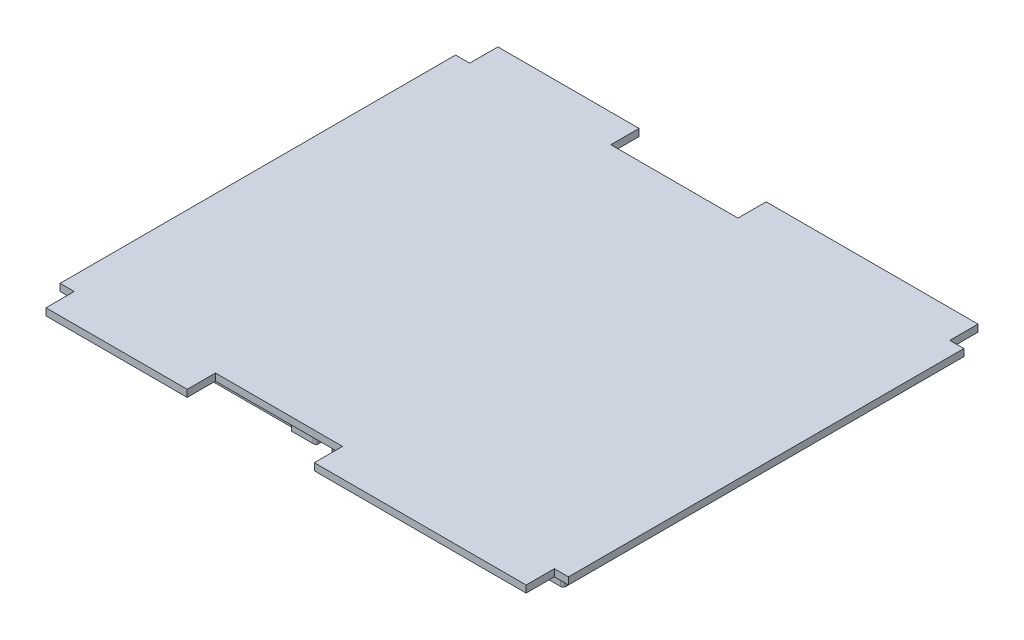
SolidWorks part; units mm, degrees
material "6061 Alloy"
ref_plane "Front Plane" through (0, 0, 0) normal (0, 0, 1) x (1, 0, 0)
ref_plane "Top Plane" through (0, 0, 0) normal (0, 1, 0) x (1, 0, 0)
ref_plane "Right Plane" through (0, 0, 0) normal (1, 0, 0) x (0, 0, -1)
sketch "Sketch1" plane through (0, 0, 0) normal (0, 1, 0) x (1, 0, 0)
  line L0 (410.2845, 0) -> (-410.2845, 0) construction
  line L1 (228.6, 177.8) -> (-228.6, 177.8) construction
  line L2 (228.6, 177.8) -> (228.6, -177.8) construction
  line L3 (228.6, -177.8) -> (-228.6, -177.8) construction
  line L4 (-228.6, 177.8) -> (-228.6, -177.8) construction
  line L5 (228.6, 177.8) -> (-228.6, -177.8) construction
  line L6 (228.6, -177.8) -> (-228.6, 177.8) construction
  line L7 (-215.9, -177.8) -> (-88.9, -177.8) construction
  line L8 (-215.9, -177.8) -> (-215.9, -203.2) construction
  line L9 (-88.9, -177.8) -> (-88.9, -203.2) construction
  line L10 (-215.9, -203.2) -> (-88.9, -203.2) construction
  line L11 (215.9, -177.8) -> (25.4, -177.8) construction
  line L12 (215.9, -177.8) -> (215.9, -203.2) construction
  line L13 (25.4, -177.8) -> (25.4, -203.2) construction
  line L14 (215.9, -203.2) -> (25.4, -203.2) construction
  line L15 (-228.6, 177.8) -> (-228.6, -177.8)
  line L16 (-228.6, -177.8) -> (-215.9, -177.8)
  line L17 (-215.9, -177.8) -> (-215.9, -203.2)
  line L18 (-215.9, -203.2) -> (-88.9, -203.2)
  line L19 (-88.9, -203.2) -> (-88.9, -177.8)
  line L20 (-88.9, -177.8) -> (25.4, -177.8)
  line L21 (25.4, -177.8) -> (25.4, -203.2)
  line L22 (25.4, -203.2) -> (215.9, -203.2)
  line L23 (215.9, -203.2) -> (215.9, -177.8)
  line L24 (215.9, -177.8) -> (228.6, -177.8)
  line L25 (228.6, -177.8) -> (228.6, 177.8)
  line L26 (215.9, 203.2) -> (25.4, 203.2) construction
  line L27 (25.4, 177.8) -> (25.4, 203.2) construction
  line L28 (215.9, 177.8) -> (215.9, 203.2) construction
  line L29 (215.9, 177.8) -> (25.4, 177.8) construction
  line L30 (-215.9, 203.2) -> (-88.9, 203.2) construction
  line L31 (-88.9, 177.8) -> (-88.9, 203.2) construction
  line L32 (-215.9, 177.8) -> (-215.9, 203.2) construction
  line L33 (-215.9, 177.8) -> (-88.9, 177.8) construction
  line L34 (228.6, 177.8) -> (-228.6, 177.8) construction
  line L35 (215.9, 177.8) -> (228.6, 177.8)
  line L36 (215.9, 203.2) -> (215.9, 177.8)
  line L37 (25.4, 203.2) -> (215.9, 203.2)
  line L38 (25.4, 177.8) -> (25.4, 203.2)
  line L39 (-88.9, 177.8) -> (25.4, 177.8)
  line L40 (-88.9, 203.2) -> (-88.9, 177.8)
  line L41 (-215.9, 203.2) -> (-88.9, 203.2)
  line L42 (-215.9, 177.8) -> (-215.9, 203.2)
  line L43 (-228.6, 177.8) -> (-215.9, 177.8)
  point P0 (0, 0)
  point P6 (-215.9, -177.8)
  point P7 (215.9, -177.8)
  point P8 (-215.9, -190.5)
  point P11 (0, 0)
  point P22 (-228.6, 0)
  point P30 (228.6, 0)
  dimension "D1" = 355.6
  dimension "D2" = 457.2
  dimension "D3" = 12.7
  dimension "D4" = 12.7
  dimension "D5" = 25.4
  dimension "D6" = 25.4
  dimension "D7" = 127
  dimension "D8" = 190.5
extrude "Boss-Extrude1" add sketch "Sketch1" along normal blind 6.35
sketch "Sketch2" plane through (0, 0, 0) normal (0, -1, 0) x (1, 0, 0)
  line L0 (0, 0) -> (0, 169.8625) construction
  line L1 (-215.9, -169.8625) -> (215.9, -169.8625) construction
  line L2 (-215.9, -169.8625) -> (-215.9, 169.8625) construction
  line L3 (-215.9, 169.8625) -> (215.9, 169.8625) construction
  line L4 (215.9, -169.8625) -> (215.9, 169.8625) construction
  line L5 (-215.9, -169.8625) -> (215.9, 169.8625) construction
  line L6 (-215.9, 169.8625) -> (215.9, -169.8625) construction
  line L7 (0, 169.8625) -> (0, -169.8625) construction
  line L8 (-193.675, 3.175) -> (-193.675, 6.35)
  line L9 (215.9, 0) -> (-215.9, 0) construction
  line L10 (0, 0) -> (215.9, 0) construction
  line L11 (-6.35, -3.175) -> (-6.35, -169.8625)
  line L12 (-28.575, -169.8625) -> (-28.575, -166.6875)
  line L13 (-6.35, -169.8625) -> (-28.575, -169.8625)
  line L14 (-28.575, -3.175) -> (-6.35, -3.175)
  line L15 (-28.575, -6.35) -> (-28.575, -3.175)
  line L16 (-193.675, -6.35) -> (-28.575, -6.35)
  line L17 (-28.575, -166.6875) -> (-193.675, -166.6875)
  line L18 (-193.675, -166.6875) -> (-193.675, -169.8625)
  line L19 (-193.675, 169.8625) -> (-215.9, 169.8625)
  line L20 (-215.9, 169.8625) -> (-215.9, 3.175)
  line L21 (-215.9, 3.175) -> (-193.675, 3.175)
  line L22 (-193.675, 166.6875) -> (-193.675, 169.8625)
  line L23 (-28.575, 166.6875) -> (-193.675, 166.6875)
  line L24 (-193.675, 6.35) -> (-28.575, 6.35)
  line L25 (-28.575, 6.35) -> (-28.575, 3.175)
  line L26 (-28.575, 3.175) -> (-6.35, 3.175)
  line L27 (-6.35, 169.8625) -> (-28.575, 169.8625)
  line L28 (-28.575, 169.8625) -> (-28.575, 166.6875)
  line L29 (-6.35, 3.175) -> (-6.35, 169.8625)
  line L30 (-215.9, -3.175) -> (-193.675, -3.175)
  line L31 (-215.9, -169.8625) -> (-215.9, -3.175)
  line L32 (-193.675, -169.8625) -> (-215.9, -169.8625)
  line L33 (-193.675, -3.175) -> (-193.675, -6.35)
  line L34 (215.9, -169.8625) -> (215.9, 169.8625) construction
  line L35 (193.675, -3.175) -> (193.675, -6.35)
  line L36 (193.675, -169.8625) -> (215.9, -169.8625)
  line L37 (215.9, -169.8625) -> (215.9, -3.175)
  line L38 (215.9, -3.175) -> (193.675, -3.175)
  line L39 (6.35, 3.175) -> (6.35, 169.8625)
  line L40 (28.575, 169.8625) -> (28.575, 166.6875)
  line L41 (6.35, 169.8625) -> (28.575, 169.8625)
  line L42 (28.575, 3.175) -> (6.35, 3.175)
  line L43 (28.575, 6.35) -> (28.575, 3.175)
  line L44 (193.675, 6.35) -> (28.575, 6.35)
  line L45 (28.575, 166.6875) -> (193.675, 166.6875)
  line L46 (193.675, 166.6875) -> (193.675, 169.8625)
  line L47 (215.9, 3.175) -> (193.675, 3.175)
  line L48 (215.9, 169.8625) -> (215.9, 3.175)
  line L49 (193.675, 169.8625) -> (215.9, 169.8625)
  line L50 (193.675, -166.6875) -> (193.675, -169.8625)
  line L51 (28.575, -166.6875) -> (193.675, -166.6875)
  line L52 (193.675, -6.35) -> (28.575, -6.35)
  line L53 (28.575, -6.35) -> (28.575, -3.175)
  line L54 (28.575, -3.175) -> (6.35, -3.175)
  line L55 (6.35, -169.8625) -> (28.575, -169.8625)
  line L56 (28.575, -169.8625) -> (28.575, -166.6875)
  line L57 (6.35, -3.175) -> (6.35, -169.8625)
  line L58 (193.675, 3.175) -> (193.675, 6.35)
  point P0 (0, 0)
  point P60 (0, 0)
  dimension "D1" = 431.8
  dimension "D2" = 339.725
  dimension "D4" = 209.55
  dimension "D5" = 22.225
  dimension "D6" = 3.175
  dimension "D7" = 22.225
  dimension "D8" = 165.1
  dimension "D9" = 3.175
  dimension "D10" = 166.6875
  dimension "D11" = 22.225
  dimension "D12" = 3.175
  dimension "D13" = 165.1
  dimension "D14" = 3.175
  dimension "D15" = 22.225
  dimension "D16" = 166.6875
extrude "Boss-Extrude2" add sketch "Sketch2" along normal blind 12.7
fillet "Fillet1" radius 2.54 16 edges at (215.9, -6.35, 169.8625) (6.35, -6.35, 3.175) (215.9, -6.35, 3.175) (215.9, -6.35, -3.175) (215.9, -6.35, -169.8625) (6.35, -6.35, -169.8625) (6.35, -6.35, -3.175) (-6.35, -6.35, -3.175) (-6.35, -6.35, -169.8625) (-215.9, -6.35, -169.8625) (-215.9, -6.35, -3.175) (-215.9, -6.35, 3.175) (-6.35, -6.35, 3.175) (-215.9, -6.35, 169.8625) (-6.35, -6.35, 169.8625) (6.35, -6.35, 169.8625)
